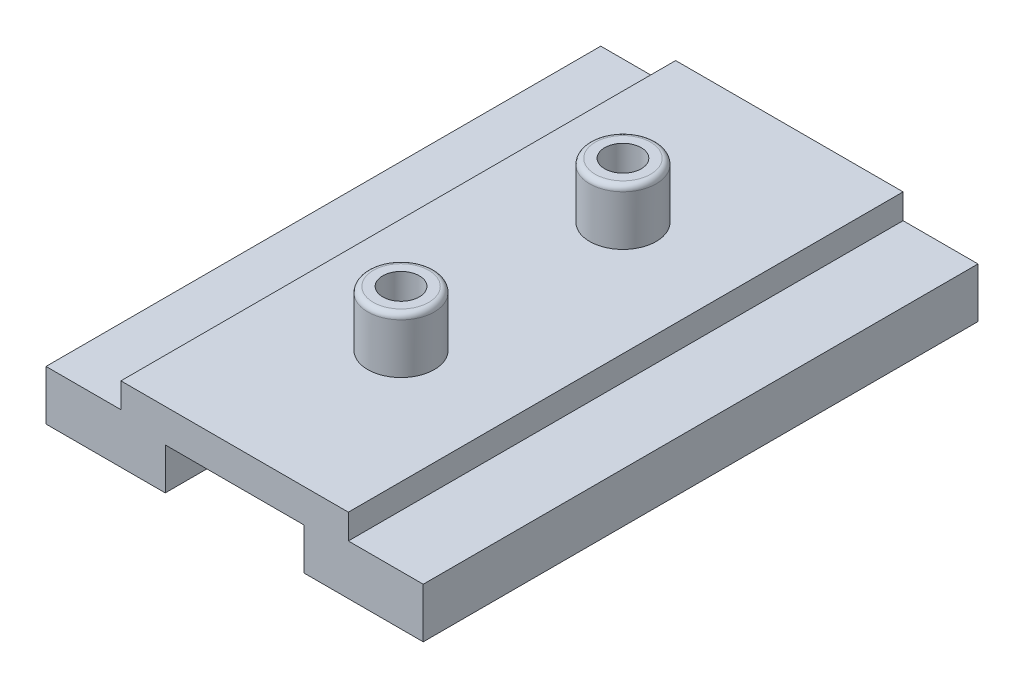
SolidWorks part; units mm, degrees
material "Zinc AC41A Alloy, As Cast"
ref_plane "Front Plane" through (0, 0, 0) normal (0, 0, 1) x (1, 0, 0)
ref_plane "Top Plane" through (0, 0, 0) normal (0, 1, 0) x (1, 0, 0)
ref_plane "Right Plane" through (0, 0, 0) normal (1, 0, 0) x (0, 0, -1)
sketch "Sketch1" plane through (0, 0, 0) normal (0, 0, 1) x (1, 0, 0)
  line L0 (0, 0) -> (0, 4.5)
  line L1 (0, 4.5) -> (6.75, 4.5)
  line L2 (6.75, 4.5) -> (6.75, 6.75)
  line L3 (6.75, 6.75) -> (27.25, 6.75)
  line L4 (27.25, 6.75) -> (27.25, 4.5)
  line L5 (27.25, 4.5) -> (34, 4.5)
  line L6 (34, 4.5) -> (34, 0)
  line L7 (10.75, 3.75) -> (23.25, 3.75)
  line L11 (23.25, 3.75) -> (23.25, 0)
  line L12 (34, 0) -> (23.25, 0)
  line L14 (10.75, 3.75) -> (10.75, 0)
  line L15 (10.75, 0) -> (0, 0)
  dimension "D1" = 4.5
  dimension "D2" = 3.75
  dimension "D3" = 10.75
  dimension "D4" = 3
  dimension "D5" = 12.5
  dimension "D6" = 10.75
  dimension "D8" = 6.75
extrude "Boss-Extrude1" add sketch "Sketch1" along normal blind 50
sketch "Sketch4" plane through (0, 6.75, 0) normal (0, 1, 0) x (1, 0, 0)
  circle A0 centre (17, -15) radius 3
  circle A1 centre (17, -35) radius 3
extrude "Boss-Extrude2" add sketch "Sketch4" along normal blind 5
hole_wizard "M4x0.7 Tapped Hole1" positions "3DSketch1" profile "Sketch5" tap size "M4x0.7" standard "Ansi Metric" end condition through all
sketch3d "3DSketch1"
  line L0 (17, 11.75, 15) -> (17, 6.75, 15) construction
  line L1 (17, 11.75, 35) -> (17, 6.75, 35) construction
  point P0 (17, 11.75, 15)
  point P4 (17, 11.75, 35)
sketch "Sketch5" plane through (17, 11.75, 15) normal (1, 0, 0) x (0, 0, 1)
  line L0 (0, 0) -> (0, 11.75)
  line L1 (0, 11.75) -> (1.65, 11.75)
  line L2 (1.65, 11.75) -> (1.65, 0)
  line L5 (1.65, 0) -> (0, 0)
  line L11 (0, -6.35) -> (0, 107.95) construction
  dimension "Thru Tap Drill Dia." = 3.3
  dimension "Thru Tap Drill Depth" = 11.75
cosmetic thread "Hole Thread1" parameters "D2"=4
cosmetic thread "Hole Thread2" parameters "D2"=4
fillet "Fillet1" radius 0.5 2 edges at (17, 11.75, 18) (17, 11.75, 38)
